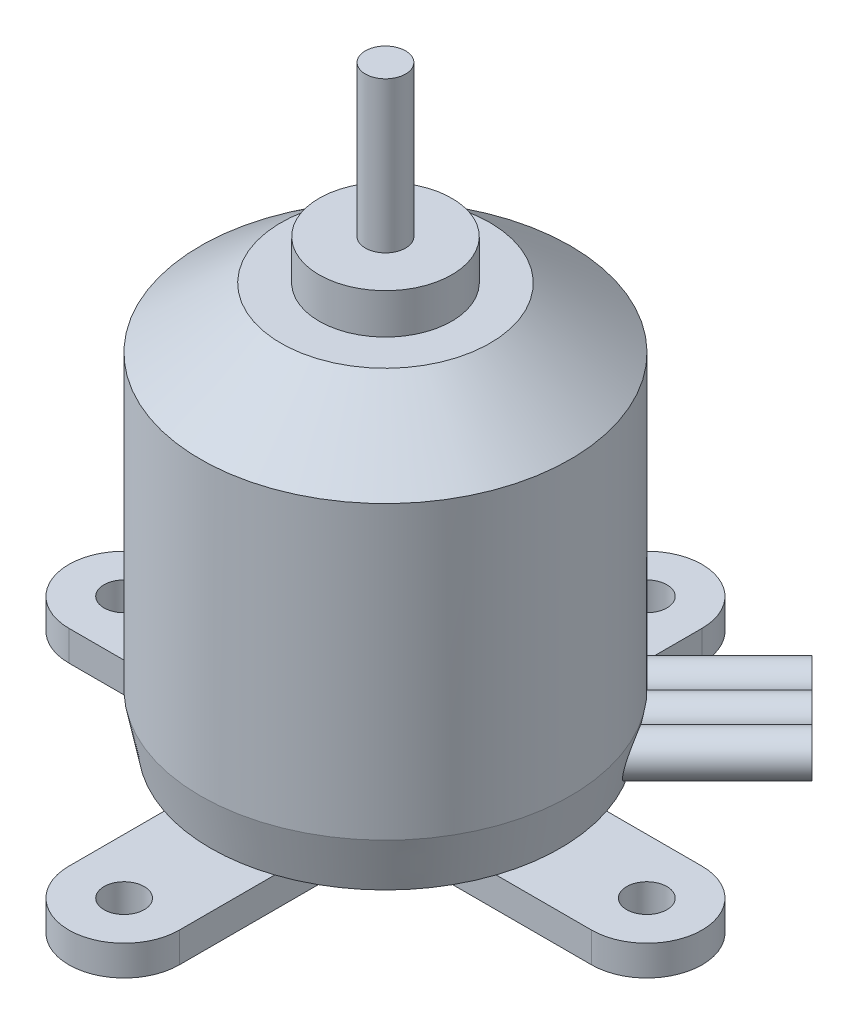
SolidWorks part; units mm, degrees
ref_plane "Front Plane" through (0, 0, 0) normal (0, 0, 1) x (1, 0, 0)
ref_plane "Top Plane" through (0, 0, 0) normal (0, 1, 0) x (1, 0, 0)
ref_plane "Right Plane" through (0, 0, 0) normal (1, 0, 0) x (0, 0, -1)
sketch "Sketch1" plane through (0, 0, 0) normal (0, 1, 0) x (1, 0, 0)
  circle A0 centre (0, 0) radius 9.2
  dimension "D1" = 18.4
extrude "Boss-Extrude1" add sketch "Sketch1" along normal blind 20
chamfer "Chamfer1" distance 3 distance2 4 1 edges at (0, 20, 9.2)
sketch "Sketch2" plane through (0, 20, 0) normal (0, 1, 0) x (1, 0, 0)
  circle A0 centre (0, 0) radius 3.3
  dimension "D1" = 6.6
extrude "Boss-Extrude2" add sketch "Sketch2" along normal blind 2 contours A0
sketch "Sketch3" plane through (0, 22, 0) normal (0, 1, 0) x (1, 0, 0)
  circle A0 centre (0, 0) radius 1
  dimension "D1" = 2
extrude "Boss-Extrude3" add sketch "Sketch3" along normal blind 7.5
chamfer "Chamfer2" distance 0.5 distance2 2.5 1 edges at (0, 0, 9.2)
sketch "Sketch4" plane through (0, 0, 0) normal (0, -1, 0) x (1, 0, 0)
  line L0 (-2.75, 2.75) -> (-2.75, 13)
  line L1 (-2.75, 13) -> (2.75, 13) construction
  line L2 (2.75, 13) -> (2.75, 2.75)
  line L3 (2.75, 2.75) -> (13, 2.75)
  line L4 (13, 2.75) -> (13, -2.75) construction
  line L5 (13, -2.75) -> (2.75, -2.75)
  line L6 (2.75, -2.75) -> (2.75, -13)
  line L7 (2.75, -13) -> (-2.75, -13) construction
  line L8 (-2.75, -13) -> (-2.75, -2.75)
  line L9 (-2.75, -2.75) -> (-13, -2.75)
  line L10 (-13, -2.75) -> (-13, 2.75) construction
  line L11 (-13, 2.75) -> (-2.75, 2.75)
  line L12 (0, 13) -> (0, -13) construction
  line L13 (0, 6.5) -> (6.5, 0) construction
  line L14 (-13, 0) -> (13, 0) construction
  line L15 (6.5, 0) -> (0, -6.5) construction
  line L16 (0, -6.5) -> (-6.5, 0) construction
  line L17 (-6.5, 0) -> (0, 6.5) construction
  arc A0 (-2.75, 13) -> (2.75, 13) centre (0, 13) cw
  arc A1 (13, 2.75) -> (13, -2.75) centre (13, 0) cw
  arc A2 (2.75, -13) -> (-2.75, -13) centre (0, -13) cw
  arc A3 (-13, -2.75) -> (-13, 2.75) centre (-13, 0) cw
  circle A4 centre (0, 13) radius 1
  circle A5 centre (13, 0) radius 1
  circle A6 centre (0, -13) radius 1
  circle A7 centre (-13, 0) radius 1
  circle A8 centre (0, 6.5) radius 1
  circle A9 centre (6.5, 0) radius 1
  circle A10 centre (0, -6.5) radius 1
  circle A11 centre (-6.5, 0) radius 1
  dimension "D1" = 2
  dimension "D2" = 13
  dimension "D4" = 2
  dimension "D5" = 6.5
  dimension "D3" = 5.5
extrude "Boss-Extrude4" add sketch "Sketch4" along normal blind 1.5
ref_plane "Plane1" through (0, 0, 0) normal (0.7071, 0, -0.7071) x (-0.7071, 0, -0.7071)
sketch "Sketch5" plane through (0, 0, 0) normal (0.7071, 0, -0.7071) x (-0.7071, 0, -0.7071)
  line L0 (-2.1, 1.25) -> (0, 1.25) construction
  line L1 (0, 1.25) -> (2.1, 1.25) construction
  line L2 (0, 1.25) -> (0, 0) construction
  line L3 (-3.8919, 0) -> (3.8919, 0) construction
  circle A0 centre (-2.1, 1.25) radius 1
  circle A1 centre (0, 1.25) radius 1
  circle A2 centre (2.1, 1.25) radius 1
  dimension "D1" = 2
  dimension "D2" = 2.1
  dimension "D3" = 1.25
extrude "Boss-Extrude5" add sketch "Sketch5" along normal blind 15
